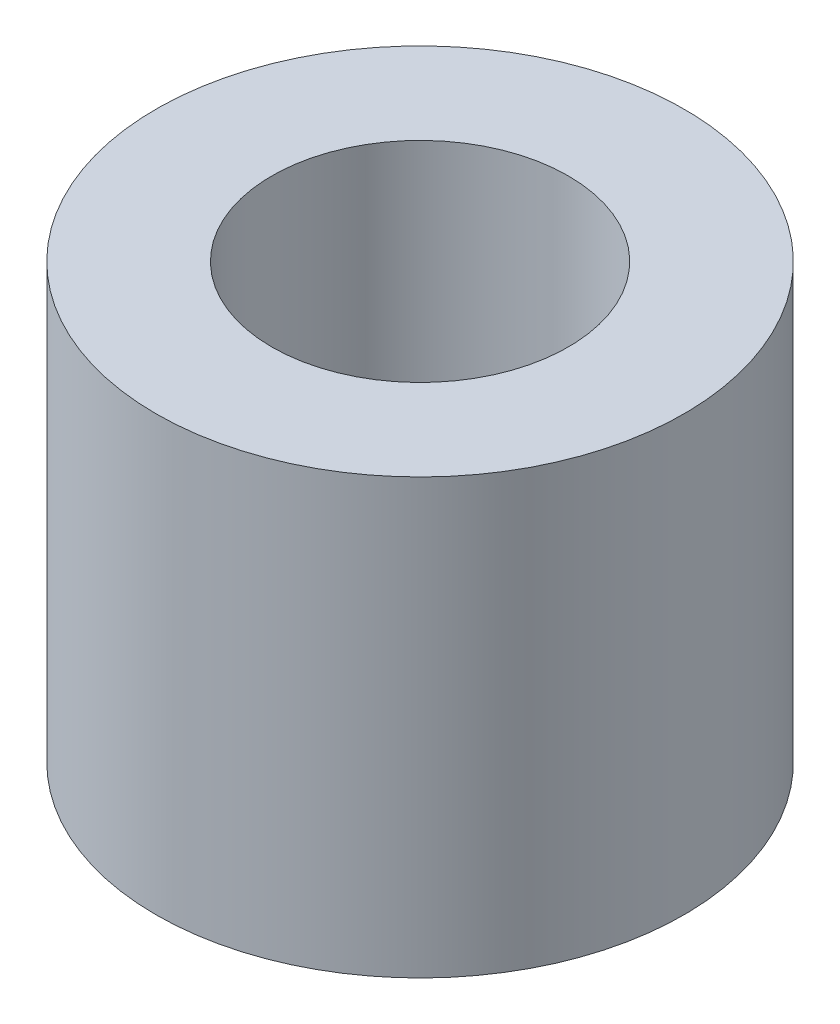
SolidWorks part; units mm, degrees
ref_plane "Front Plane" through (0, 0, 0) normal (0, 0, 1) x (1, 0, 0)
ref_plane "Top Plane" through (0, 0, 0) normal (0, 1, 0) x (1, 0, 0)
ref_plane "Right Plane" through (0, 0, 0) normal (1, 0, 0) x (0, 0, -1)
sketch "Sketch1" plane through (0, 0, 0) normal (0, 1, 0) x (1, 0, 0)
  circle A0 centre (0, 0) radius 1.025
  circle A1 centre (0, 0) radius 1.825
  dimension "D1" = 2.05
  dimension "D2" = 3.65
extrude "Boss-Extrude1" add sketch "Sketch1" along normal blind 3
